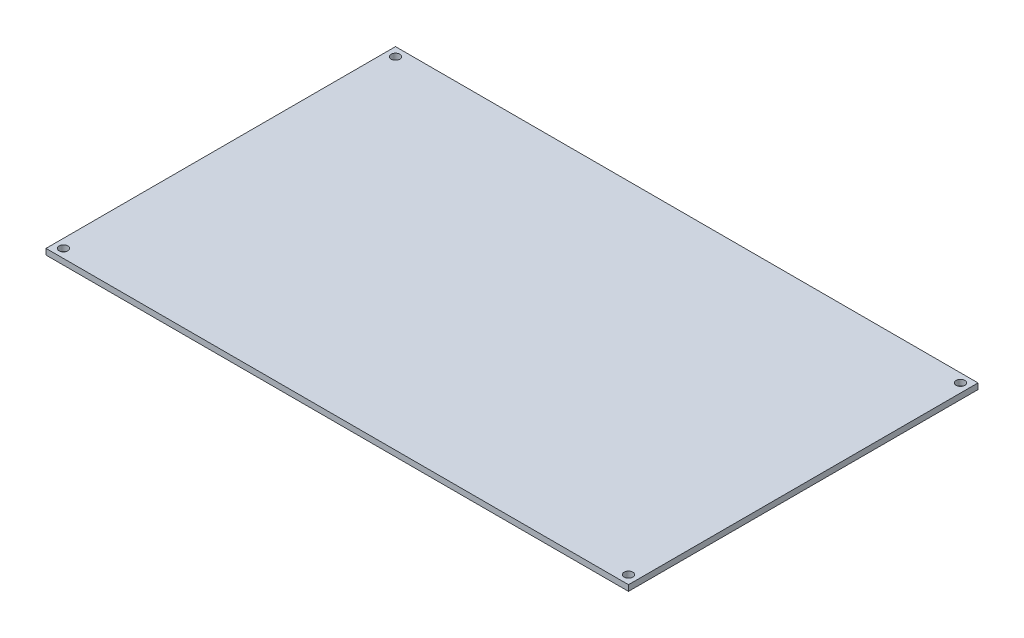
SolidWorks part; units mm, degrees
ref_plane "Front Plane" through (0, 0, 0) normal (0, 0, 1) x (1, 0, 0)
ref_plane "Top Plane" through (0, 0, 0) normal (0, 1, 0) x (1, 0, 0)
ref_plane "Right Plane" through (0, 0, 0) normal (1, 0, 0) x (0, 0, -1)
sketch "Sketch1" plane through (0, 0, 0) normal (0, 1, 0) x (1, 0, 0)
  line L1 (0, 0) -> (200, 0)
  line L2 (0, 0) -> (0, 120)
  line L3 (0, 120) -> (200, 120)
  line L4 (200, 0) -> (200, 120)
  dimension "D1" = 120
  dimension "D2" = 200
extrude "Boss-Extrude1" add sketch "Sketch1" along normal blind 2
sketch "Sketch2" plane through (0, 2, 0) normal (0, 1, 0) x (1, 0, 0)
  line L0 (200, 0) -> (200, 120) construction
  line L1 (200, 120) -> (0, 120) construction
  line L2 (0, 0) -> (200, 0) construction
  line L3 (0, 120) -> (0, 0) construction
  circle A0 centre (197, 117) radius 1.5
  circle A1 centre (197, 3) radius 1.5
  circle A2 centre (3, 3) radius 1.5
  circle A3 centre (3, 117) radius 1.5
  dimension "D3" = 3
  dimension "D5" = 3
  dimension "D6" = 3
  dimension "D8" = 3
  dimension "D1" = 3
  dimension "D2" = 3
  dimension "D4" = 3
  dimension "D7" = 3
  dimension "D9" = 3
  dimension "D10" = 3
extrude "Cut-Extrude1" cut sketch "Sketch2" against normal blind 3
